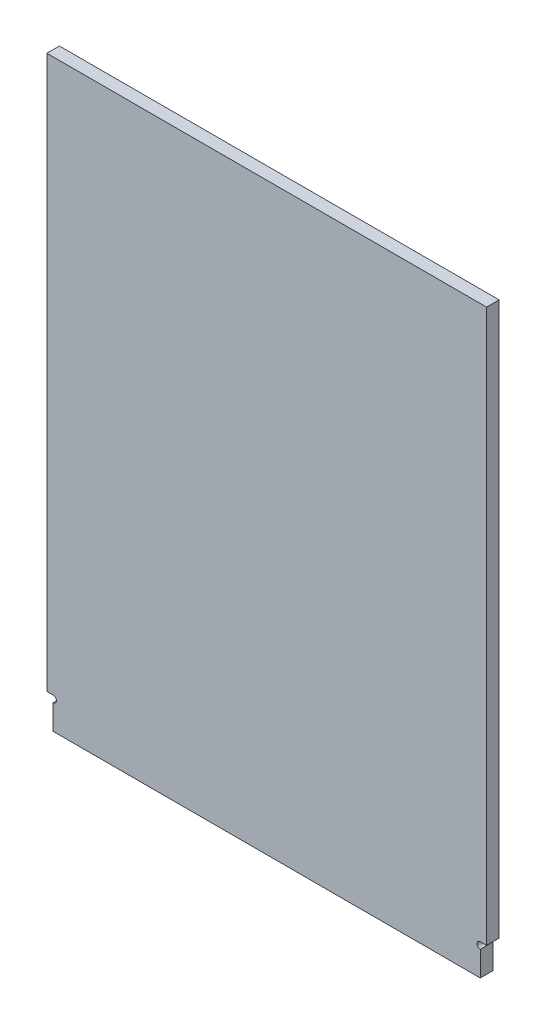
SolidWorks part; units mm, degrees
ref_plane "Front Plane" through (0, 0, 0) normal (0, 0, 1) x (1, 0, 0)
ref_plane "Top Plane" through (0, 0, 0) normal (0, 1, 0) x (1, 0, 0)
ref_plane "Right Plane" through (0, 0, 0) normal (1, 0, 0) x (0, 0, -1)
sketch "Sketch1" plane through (0, 0, 0) normal (0, 0, 1) x (1, 0, 0)
  line L1 (222.25, -304.8) -> (-222.25, -304.8)
  line L2 (222.25, -304.8) -> (222.25, 304.8)
  line L3 (222.25, 304.8) -> (-222.25, 304.8)
  line L4 (-222.25, -304.8) -> (-222.25, 304.8)
  line L5 (222.25, -304.8) -> (-222.25, 304.8) construction
  line L6 (222.25, 304.8) -> (-222.25, -304.8) construction
  line L9 (-209.55, 304.8) -> (-222.25, 304.8) construction
  point P0 (0, 0)
  dimension "D1" = 444.5
  dimension "D2" = 609.6
extrude "Boss-Extrude1" add sketch "Sketch1" along normal blind 12.7
sketch "Sketch2" plane through (0, 0, 12.7) normal (0, 0, 1) x (1, 0, 0)
  line L0 (222.25, 304.8) -> (-222.25, 304.8) construction
  line L1 (-190.5, 292.1) -> (-222.25, 292.1) construction
  line L2 (-190.5, 304.8) -> (-165.1, 304.8)
  line L3 (-190.5, 304.8) -> (-190.5, 292.1)
  line L4 (-190.5, 292.1) -> (-165.1, 292.1)
  line L5 (-165.1, 304.8) -> (-165.1, 292.1)
  line L6 (-222.25, 304.8) -> (-222.25, -304.8) construction
  circle A0 centre (-187.198, 292.1) radius 3.302
  circle A1 centre (-168.402, 292.1) radius 3.302
  line M10 (222.25, 304.8) -> (-222.25, 304.8)
  dimension "D4" = 6.604
  dimension "D5" = 6.604
  dimension "D1" = 25.4
  dimension "D2" = 12.7
  dimension "D3" = 31.75
extrude "Cut-Extrude1" cut sketch "Sketch2" against normal through all contours A1 L5 L3 A0 L4 M10 | L4 A0 | L4 A0 | L4 A1 | L4 A1
pattern_linear "LPattern1" count 8 spacing 50.8 along (1, 0, 0) of "Cut-Extrude1"
ref_plane "Plane1" through (0, 0, 0) normal (1, 0, 0) x (0, 0, -1)
ref_plane "Plane2" through (0, 0, 0) normal (0, 1, 0) x (1, 0, 0)
mirror "Mirror2" [suppressed] about plane through (0, 0, 0) normal (0, 1, 0)
sketch "Sketch3" plane through (0, 0, 12.7) normal (0, 0, 1) x (1, 0, 0)
  line L1 (-222.25, -304.8) -> (-215.9, -304.8)
  line L2 (-222.25, -304.8) -> (-222.25, -266.7)
  line L3 (-222.25, -266.7) -> (-215.9, -266.7)
  line L4 (-215.9, -304.8) -> (-215.9, -266.7)
  circle A0 centre (-215.9, -270.002) radius 3.302
  dimension "D3" = 6.604
  dimension "D1" = 38.1
  dimension "D2" = 6.35
extrude "Cut-Extrude2" cut sketch "Sketch3" against normal through all contours A0 L3 L2 L1 L4
mirror "Mirror3" about plane through (0, 0, 0) normal (1, 0, 0) of "Cut-Extrude2"
sketch "Sketch4" plane through (0, 0, 12.7) normal (0, 0, 1) x (1, 0, 0)
  line L0 (222.25, -266.7) -> (222.25, 304.8) construction
  line L1 (-222.25, 304.8) -> (222.25, 304.8)
  line L2 (-222.25, 304.8) -> (-222.25, 292.1)
  line L3 (-222.25, 292.1) -> (222.25, 292.1)
  line L4 (222.25, 304.8) -> (222.25, 292.1)
  dimension "D1" = 12.7
extrude "Cut-Extrude3" cut sketch "Sketch4" against normal through all
sketch "Sketch5" plane through (0, 0, 12.7) normal (0, 0, 1) x (1, 0, 0)
  line L0 (222.25, -266.7) -> (222.25, 292.1) construction
  line L1 (-222.25, 292.1) -> (222.25, 292.1)
  line L2 (-222.25, 292.1) -> (-222.25, 273.6681)
  line L3 (-222.25, 273.6681) -> (222.25, 273.6681)
  line L4 (222.25, 292.1) -> (222.25, 273.6681)
extrude "Boss-Extrude2" add sketch "Sketch5" against normal blind 12.7
sketch "Sketch6" [suppressed] plane through (0, 0, 12.7) normal (0, 0, 1) x (1, 0, 0)
  line L1 (-165.1, -304.8) -> (-229.7937, -304.8)
  line L2 (-165.1, -304.8) -> (-165.1, -292.1)
  line L3 (-165.1, -292.1) -> (-229.7937, -292.1)
  line L4 (-229.7937, -304.8) -> (-229.7937, -292.1)
  dimension "D1" = 12.7
extrude "Cut-Extrude4" [suppressed] cut sketch "Sketch6" against normal through all
mirror "Mirror4" [suppressed] about plane through (0, 0, 0) normal (1, 0, 0)
sketch "Sketch7" plane through (0, -304.8, 0) normal (0, -1, 0) x (1, 0, 0)
  line L1 (-222.25, 12.7) -> (222.25, 12.7)
  line L2 (-222.25, 12.7) -> (-222.25, 0)
  line L3 (-222.25, 0) -> (222.25, 0)
  line L4 (222.25, 12.7) -> (222.25, 0)
extrude "Cut-Extrude5" cut sketch "Sketch7" against normal blind 6.35
